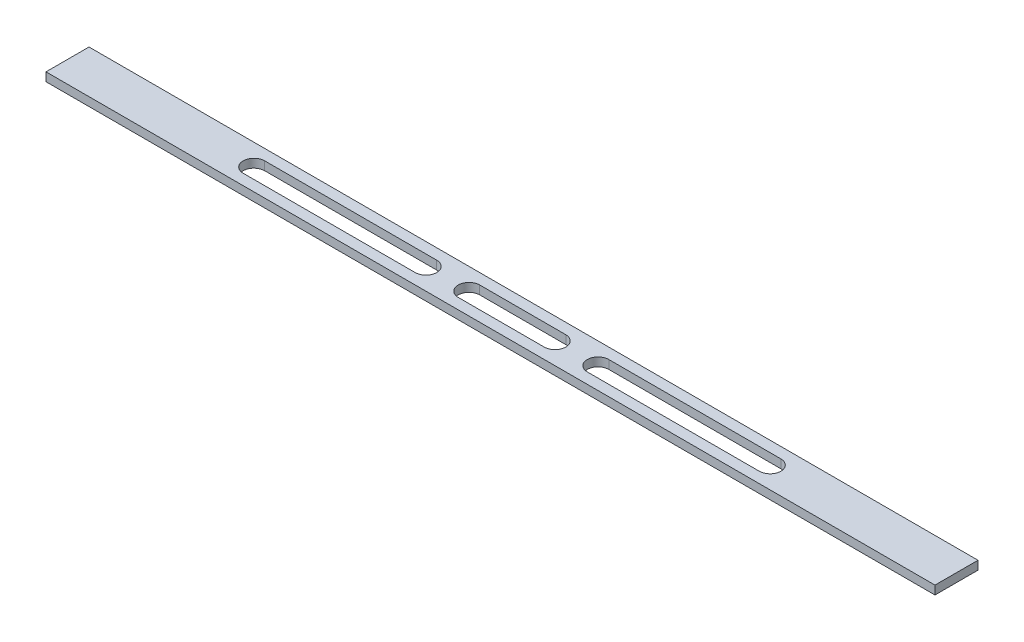
SolidWorks part; units mm, degrees
material "Q235"
ref_plane "前视基准面" through (0, 0, 0) normal (0, 0, 1) x (1, 0, 0)
ref_plane "上视基准面" through (0, 0, 0) normal (0, 1, 0) x (1, 0, 0)
ref_plane "右视基准面" through (0, 0, 0) normal (1, 0, 0) x (0, 0, -1)
sketch "草图1" plane through (0, 0, 0) normal (0, 1, 0) x (1, 0, 0)
  line L0 (310, 15) -> (-310, -15) construction
  line L1 (-310, 15) -> (310, 15)
  line L2 (-310, 15) -> (-310, -15)
  line L3 (-310, -15) -> (310, -15)
  line L4 (310, 15) -> (310, -15)
  dimension "D1" = 620
  dimension "D2" = 30
extrude "凸台-拉伸1" add sketch "草图1" along normal blind 6
sketch "草图2" plane through (0, 6, 0) normal (0, 1, 0) x (1, 0, 0)
  line L0 (30, 0) -> (-30, 0) construction
  line L1 (30, -7.5) -> (-30, -7.5)
  line L2 (30, 7.5) -> (-30, 7.5)
  line L3 (-60, 0) -> (-180, 0) construction
  line L4 (-60, -7.5) -> (-180, -7.5)
  line L5 (-60, 7.5) -> (-180, 7.5)
  line L6 (60, 0) -> (180, 0) construction
  line L7 (60, 7.5) -> (180, 7.5)
  line L8 (60, -7.5) -> (180, -7.5)
  arc A0 (30, -7.5) -> (30, 7.5) centre (30, 0) ccw
  arc A1 (-30, 7.5) -> (-30, -7.5) centre (-30, 0) ccw
  arc A2 (-60, -7.5) -> (-60, 7.5) centre (-60, 0) ccw
  arc A3 (-180, 7.5) -> (-180, -7.5) centre (-180, 0) ccw
  arc A4 (60, 7.5) -> (60, -7.5) centre (60, 0) ccw
  arc A5 (180, -7.5) -> (180, 7.5) centre (180, 0) ccw
  point P3 (0, 0)
  point P9 (-120, 0)
  point P18 (120, 0)
  dimension "D1" = 7.5
  dimension "D4" = 30
  dimension "D5" = 30
  dimension "D6" = 7.5
  dimension "D2" = 120
  dimension "D3" = 60
extrude "切除-拉伸1" cut sketch "草图2" against normal through all
